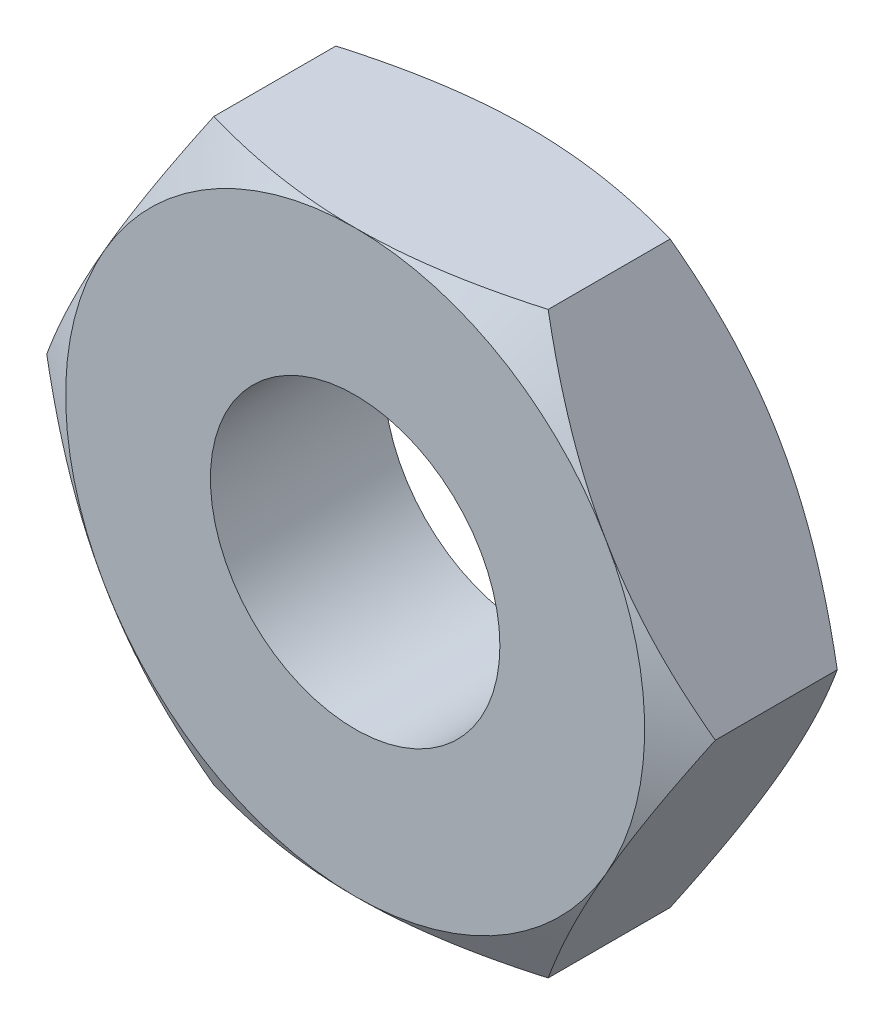
SolidWorks part; units mm, degrees
material "AISI 316 (A4) Annealed Stainless Bar"
ref_plane "Front" through (0, 0, 0) normal (0, 0, 1) x (1, 0, 0)
ref_plane "Top" through (0, 0, 0) normal (0, 1, 0) x (1, 0, 0)
ref_plane "Right" through (0, 0, 0) normal (1, 0, 0) x (0, 0, -1)
sketch "HexSketch1" plane through (0, 0, 0) normal (0, 0, 1) x (1, 0, 0)
  line L1 (1.1547, 2) -> (-1.1547, 2)
  line L2 (-1.1547, 2) -> (-2.3094, 0)
  line L3 (-2.3094, 0) -> (-1.1547, -2)
  line L4 (-1.1547, -2) -> (1.1547, -2)
  line L5 (1.1547, -2) -> (2.3094, 0)
  line L6 (2.3094, 0) -> (1.1547, 2)
  circle A0 centre (0, 0) radius 2 construction
  dimension "A/F" = 4
extrude "Hex" add sketch "HexSketch1" against normal blind 1.2
ref_plane "Nut_Top_Plane" through (0, 0, 0) normal (0, 0, 1) x (1, 0, 0)
ref_plane "Collar_Top_Plane" through (0, 0, 4.8) normal (0, 0, -1) x (-1, 0, 0)
sketch "Lock Collar BossSketch2" plane through (0, 0, 0) normal (0, 0, 1) x (1, 0, 0)
  circle A0 centre (0, 0) radius 2
  dimension "A/F" = 4
sketch "Plastic_SleeveSketch5" plane through (0, 0, 4.8) normal (0, 0, -1) x (-1, 0, 0)
  circle A0 centre (0, 0) radius 1
  circle A1 centre (0, 0) radius 4
  dimension "INSERT_OD" = 8
  dimension "thread" = 2
ref_axis "Axis1" through (0, 0, 50) along (0, 0, -1)
sketch "Thread_BoreSketch4" plane through (0, 0, 0) normal (0, 0, 1) x (1, 0, 0)
  circle A0 centre (0, 0) radius 1
  dimension "thread" = 2
extrude "Thread_Bore" cut sketch "Thread_BoreSketch4" against normal through all
ref_plane "CORNERSPlane3" through (0, 0, 0) normal (0.866, 0.5, 0) x (0, 0, -1)
sketch "NUT_CHAMFERSketch10" plane through (0, 0, 0) normal (0.866, 0.5, 0) x (0, 0, -1)
  line L0 (0, 2) -> (0.1786, 2.3094)
  line L1 (1.2, 2.3094) -> (0, 2.3094) construction
  line L2 (0.1786, 2.3094) -> (0, 2.3094)
  line L3 (0, 2.3094) -> (0, 2)
  line L4 (0.6, 2.3094) -> (0.6, -2.3094) construction
  line L5 (1.2, -2.3094) -> (0, -2.3094) construction
  line L6 (1.2, 2) -> (1.0214, 2.3094)
  line L7 (1.0214, 2.3094) -> (1.2, 2.3094)
  line L8 (1.2, 2.3094) -> (1.2, 2)
  dimension "D1" = 30
  dimension "D2" = 2
revolve "NUT_CHAMFER" cut sketch "NUT_CHAMFERSketch10" angle 360 about axis through (0, 0, 50) along (0, 0, -1)
equation "\"D2@NUT_CHAMFERSketch10\" = \"A/F\"/2"
